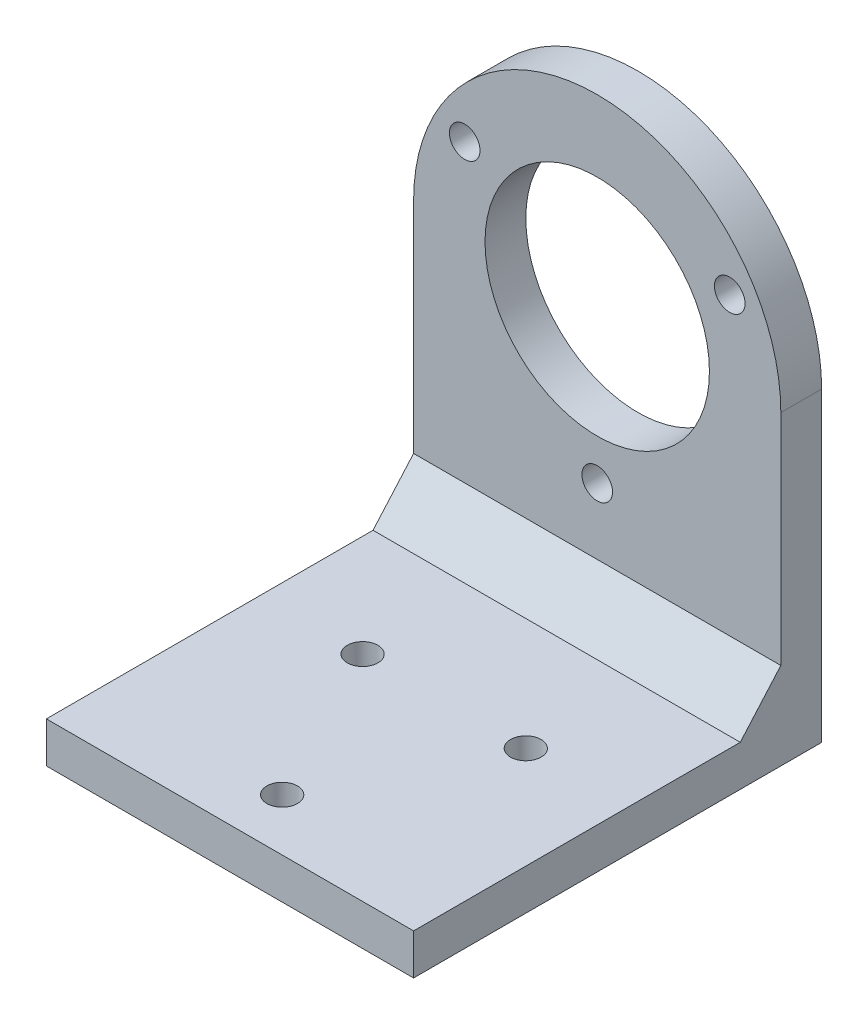
SolidWorks part; units mm, degrees
ref_plane "前视基准面" through (0, 0, 0) normal (0, 0, 1) x (1, 0, 0)
ref_plane "上视基准面" through (0, 0, 0) normal (0, 1, 0) x (1, 0, 0)
ref_plane "右视基准面" through (0, 0, 0) normal (1, 0, 0) x (0, 0, -1)
sketch "Sketch1" plane through (0, 0, 0) normal (0, 0, 1) x (1, 0, 0)
  line L2 (-38.9004, 21.8309) -> (-38.9004, -8.1691)
  line L3 (-38.9004, -8.1691) -> (-2.9004, -8.1691)
  line L4 (-2.9004, 21.8309) -> (-2.9004, -8.1691)
  arc A0 (-2.9004, 21.8309) -> (-38.9004, 21.8309) centre (-20.9004, 21.8309) ccw
extrude "Boss-Extrude1" add sketch "Sketch1" along normal blind 4
sketch "Sketch3" plane through (0, 0, 0) normal (0, 0, 1) x (1, 0, 0)
  line L0 (-38.9004, 21.8309) -> (-38.9004, -8.1691) construction
  line L1 (-2.9004, -8.1691) -> (-38.9004, -8.1691)
  line L2 (-2.9004, -8.1691) -> (-2.9004, -4.1691)
  line L3 (-2.9004, -4.1691) -> (-38.9004, -4.1691)
  line L4 (-38.9004, -8.1691) -> (-38.9004, -4.1691)
extrude "Boss-Extrude2" add sketch "Sketch3" along normal blind 40
sketch "Sketch4" plane through (0, 0, 0) normal (0, 0, 1) x (1, 0, 0)
  circle A0 centre (-20.9004, 21.8309) radius 11
  circle A1 centre (-20.9004, 6.8309) radius 1.5
  circle A2 centre (-33.8907, 29.3309) radius 1.5
  circle A3 centre (-7.91, 29.3309) radius 1.5
  point P11 (-20.9004, 21.8309)
  dimension "D1" = 3
extrude "Cut-Extrude1" cut sketch "Sketch4" along normal blind 22
sketch "Sketch5" plane through (0, 0, 0) normal (0, 1, 0) x (1, 0, 0)
  circle A0 centre (-28.9004, -19) radius 1.5
  circle A1 centre (-12.9004, -19) radius 1.5
  circle A2 centre (-20.9004, -34.884) radius 1.5
extrude "Cut-Extrude2" cut sketch "Sketch5" against normal blind 10
sketch "Sketch6" plane through (0, 0, 0) normal (1, 0, 0) x (0, 0, -1)
  line L0 (-4, 0.3645) -> (-7.978, -4.1691)
  line L1 (-4, -4.1691) -> (-4, 21.8309) construction
  line L2 (-40, -4.1691) -> (-4, -4.1691) construction
  line L3 (-4, 0.3645) -> (-4, -4.1691)
  line L4 (-4, -4.1691) -> (-7.978, -4.1691)
sketch "Sketch7" plane through (-2.9004, 0, 0) normal (1, 0, 0) x (0, 0, -1)
  line L0 (-4, 0.3645) -> (-7.978, -4.1691)
  line L1 (-7.978, -4.1691) -> (-4, -4.1691)
  line L2 (-4, -4.1691) -> (-4, 0.3645)
extrude "Boss-Extrude4" add sketch "Sketch7" against normal blind 36
